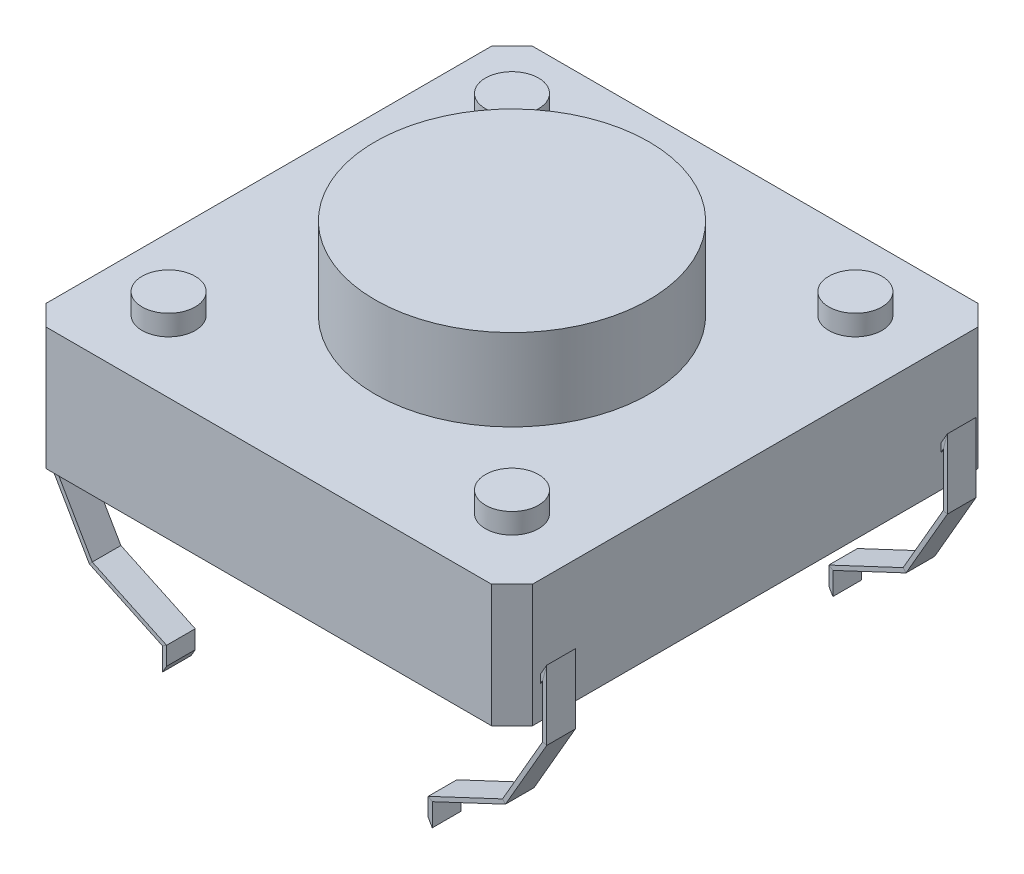
SolidWorks part; units mm, degrees
ref_plane "Front Plane" through (0, 0, 0) normal (0, 0, 1) x (1, 0, 0)
ref_plane "Top Plane" through (0, 0, 0) normal (0, 1, 0) x (1, 0, 0)
ref_plane "Right Plane" through (0, 0, 0) normal (1, 0, 0) x (0, 0, -1)
sketch "Sketch1" plane through (0, 0, 0) normal (0, 1, 0) x (1, 0, 0)
  line L1 (-5.95, -5.95) -> (5.95, -5.95)
  line L2 (-5.95, -5.95) -> (-5.95, 5.95)
  line L3 (-5.95, 5.95) -> (5.95, 5.95)
  line L4 (5.95, -5.95) -> (5.95, 5.95)
  line L5 (-5.95, -5.95) -> (5.95, 5.95) construction
  line L6 (-5.95, 5.95) -> (5.95, -5.95) construction
  point P0 (0, 0)
  dimension "D1" = 11.9
  dimension "D2" = 11.9
extrude "Boss-Extrude1" add sketch "Sketch1" along normal blind 3
chamfer "Chamfer1" distance 0.5 angle 45 4 edges at (5.95, 1.5, -5.95) (-5.95, 1.5, -5.95) (-5.95, 1.5, 5.95) (5.95, 1.5, 5.95)
sketch "Sketch3" plane through (0, 3, 0) normal (0, 1, 0) x (1, 0, 0)
  circle A0 centre (0, 0) radius 3.35
  dimension "D1" = 6.7
extrude "Boss-Extrude2" add sketch "Sketch3" along normal blind 2
sketch "Sketch4" plane through (0, 3, 0) normal (0, 1, 0) x (1, 0, 0)
  line L0 (4.2, -4.2) -> (-4.2, 4.2) construction
  line L1 (-4.2, -4.2) -> (4.2, -4.2) construction
  line L2 (-4.2, -4.2) -> (-4.2, 4.2) construction
  line L3 (-4.2, 4.2) -> (4.2, 4.2) construction
  line L4 (4.2, -4.2) -> (4.2, 4.2) construction
  line L5 (5.45, 5.95) -> (-5.45, 5.95) construction
  line L6 (5.95, -5.45) -> (5.95, 5.45) construction
  circle A0 centre (4.2, 4.2) radius 0.65
  circle A1 centre (4.2, -4.2) radius 0.65
  circle A2 centre (-4.2, 4.2) radius 0.65
  circle A3 centre (-4.2, -4.2) radius 0.65
  point P2 (-4.4012, 3.698)
  point P3 (4.4793, -4.4012)
  point P6 (0, 0)
  point P13 (0, 0)
  dimension "D1" = 1.3
  dimension "D2" = 1.75
  dimension "D3" = 1.75
sketch "Sketch5" plane through (0, 3, 0) normal (0, 1, 0) x (1, 0, 0)
  circle A0 centre (-2.25, -2.25) radius 0.5
extrude "Boss-Extrude6" add sketch "Sketch4" along normal blind 0.5
extrude "Boss-Extrude7" [suppressed] add sketch "Sketch5" along normal blind 0.5
sketch "Sketch6" plane through (-5.95, 0, 0) normal (-1, 0, 0) x (0, 0, 1)
  line L0 (-5.45, 0) -> (5.45, 0) construction
  line L1 (-5.25, 1) -> (-4.55, 1)
  line L2 (-5.25, 1) -> (-5.25, 0.8)
  line L3 (-5.25, 0.8) -> (-4.55, 0.8)
  line L4 (-4.55, 1) -> (-4.55, 0.8)
  line L5 (-5.25, 1) -> (-4.55, 0.8) construction
  line L6 (-5.25, 0.8) -> (-4.55, 1) construction
  line L7 (-5.45, 3) -> (-5.45, 0) construction
  point P0 (-4.9, 0.9)
  dimension "D1" = 0.7
  dimension "D2" = 0.2
  dimension "D3" = 1
  dimension "D4" = 0.2
sketch "Sketch7" plane through (0, 0, 0) normal (0, 0, 1) x (1, 0, 0)
  line L0 (-5.95, 0.9) -> (-6.05, 1.0732)
  line L1 (-6.05, 1.0732) -> (-6.05, -0.4268)
  line L2 (-6.05, -0.4268) -> (-5.0536, -2.1526)
  line L3 (-5.0536, -2.1526) -> (-3.25, -3)
  line L4 (-3.25, -3) -> (-3.25, -3.5)
  line L5 (5.45, 0) -> (-5.45, 0) construction
  line L6 (-5.95, 3) -> (-5.95, 0) construction
  dimension "D1" = 3.5
  dimension "D2" = 0.1
  dimension "D3" = 3.25
  dimension "D4" = 0.5
  dimension "D5" = 1.5
  dimension "D6" = 150
  dimension "D7" = 30
sweep "Sweep1" add profiles "Sketch6" path "Sketch7"
mirror "Mirror1" about plane through (0, 0, 0) normal (0, 0, 1) of "Sweep1"
mirror "Mirror2" about plane through (0, 0, 0) normal (1, 0, 0) of "Mirror1", "Sweep1"
sketch "Sketch8" plane through (0, 0, 0) normal (1, 0, 0) x (0, 0, -1)
  line L0 (-5.25, -3.3092) -> (-5.25, -3.4134)
  line L1 (-5.25, -3.0318) -> (-5.25, -3.5866) construction
  line L2 (-5.25, -3.4134) -> (-4.55, -3.4134)
  line L3 (-4.55, -3.4134) -> (-4.55, -3.3092)
  line L4 (-4.55, -3.0318) -> (-4.55, -3.5866) construction
  line L5 (-4.55, -3.3092) -> (-3.3724, -4.8805)
  line L6 (-3.5227, -5.0117) -> (-5.25, -3.3092)
  arc A0 (-3.3724, -4.8805) -> (-3.5227, -5.0117) centre (-3.4525, -4.9405) cw
  dimension "D1" = 0.1
extrude "Cut-Extrude1" [suppressed] cut sketch "Sketch8" against normal through all and the other way through all
mirror "Mirror3" [suppressed] about plane through (0, 0, 0) normal (0, 0, 1)
